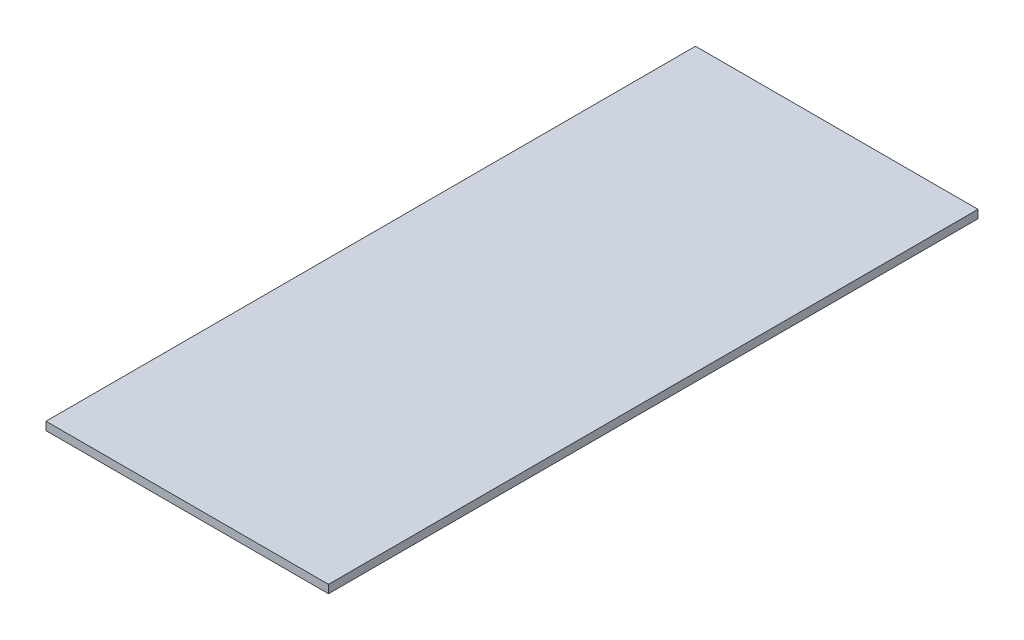
SolidWorks part; units mm, degrees
ref_plane "Front Plane" through (0, 0, 0) normal (0, 0, 1) x (1, 0, 0)
ref_plane "Top Plane" through (0, 0, 0) normal (0, 1, 0) x (1, 0, 0)
ref_plane "Right Plane" through (0, 0, 0) normal (1, 0, 0) x (0, 0, -1)
sketch "Sketch1" plane through (0, 0, 0) normal (0, 1, 0) x (1, 0, 0)
  line L1 (-13.81, 31.75) -> (13.81, 31.75)
  line L2 (-13.81, 31.75) -> (-13.81, -31.75)
  line L3 (-13.81, -31.75) -> (13.81, -31.75)
  line L4 (13.81, 31.75) -> (13.81, -31.75)
  dimension "D1" = 63.5
  dimension "D2" = 27.62
  dimension "D3" = 13.81
  dimension "D4" = 31.75
extrude "Boss-Extrude1" add sketch "Sketch1" along normal blind 0.8
